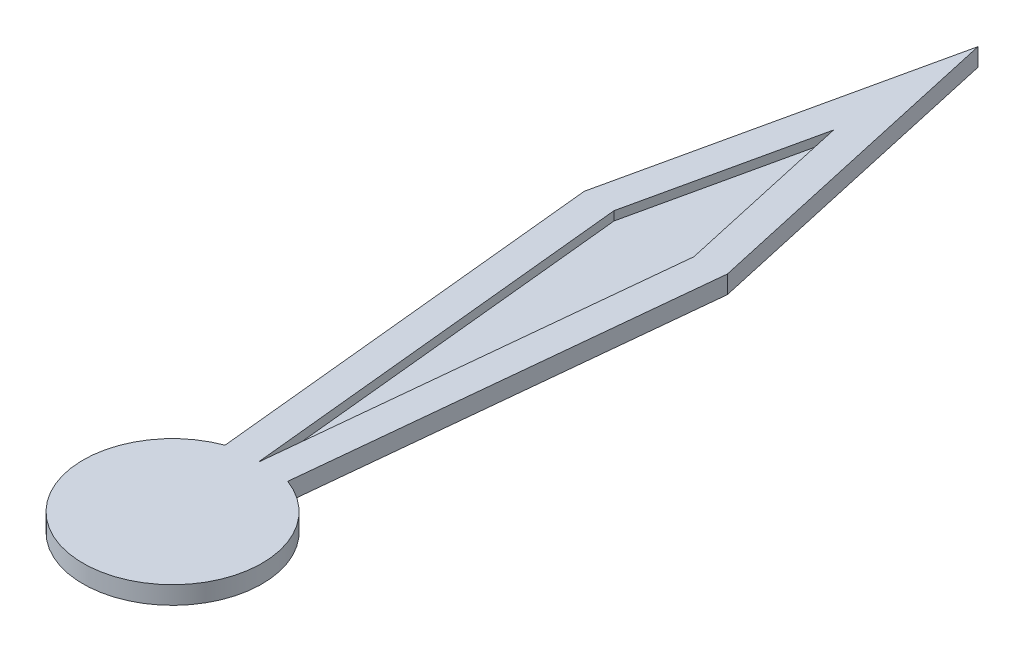
SolidWorks part; units mm, degrees
ref_plane "Front Plane" through (0, 0, 0) normal (0, 0, 1) x (1, 0, 0)
ref_plane "Top Plane" through (0, 0, 0) normal (0, 1, 0) x (1, 0, 0)
ref_plane "Right Plane" through (0, 0, 0) normal (1, 0, 0) x (0, 0, -1)
sketch "Sketch1" plane through (0, 0, 0) normal (0, 1, 0) x (1, 0, 0)
  line L0 (0, 0) -> (0, 9) construction
  line L1 (0, 9) -> (0.8, 5.4)
  line L2 (-0.8, 5.4) -> (-0.35, 0.9367)
  line L3 (0.8, 5.4) -> (0.35, 0.9367)
  line L4 (0, 9) -> (-0.8, 5.4)
  arc A0 (-0.35, 0.9367) -> (0.35, 0.9367) centre (0, 0) ccw
  dimension "D1" = 2
  dimension "D2" = 9
  dimension "D3" = 1.6
  dimension "D4" = 3.6
  dimension "D5" = 0.7
extrude "Extrude1" add sketch "Sketch1" along normal blind 0.2
sketch "Sketch2" plane through (0, 0.2, 0) normal (0, 1, 0) x (1, 0, 0)
  line L10 (-0.0018, 0.9719) -> (0.0018, 0.9719)
  line L14 (-0.4461, 5.3791) -> (-0.0018, 0.9719)
  line L15 (0.0018, 0.9719) -> (0.4461, 5.3791)
  line L16 (0.4461, 5.3791) -> (0, 7.3866)
  line L17 (0, 7.3866) -> (-0.4461, 5.3791)
  line L18 (-0.4461, 5.3791) -> (-0.0018, 0.9719)
  line L19 (0.0018, 0.9719) -> (0.4461, 5.3791)
  line L20 (0.4461, 5.3791) -> (0, 7.3866)
  line L21 (0, 7.3866) -> (-0.4461, 5.3791)
  dimension "D1" = 0.35
extrude "Extrude2" cut sketch "Sketch2" against normal blind 0.1
